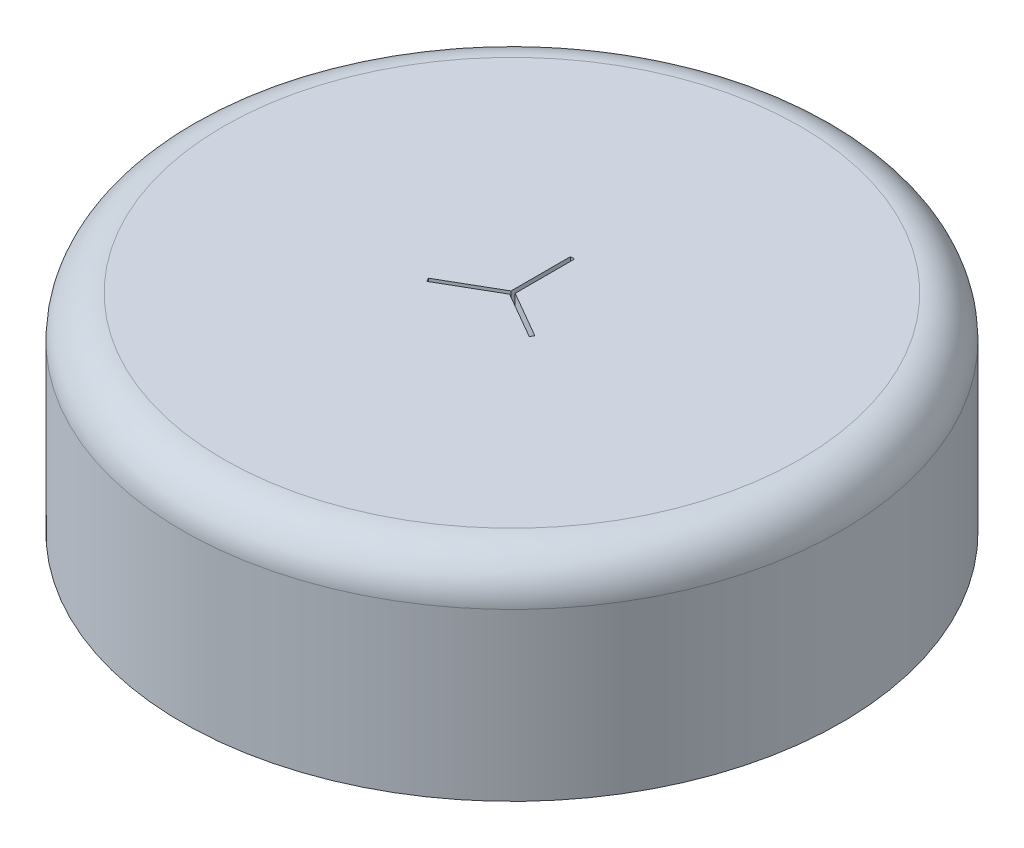
SolidWorks part; units mm, degrees
ref_plane "前视基准面" through (0, 0, 0) normal (0, 0, 1) x (1, 0, 0)
ref_plane "上视基准面" through (0, 0, 0) normal (0, 1, 0) x (1, 0, 0)
ref_plane "右视基准面" through (0, 0, 0) normal (1, 0, 0) x (0, 0, -1)
sketch "草图1" plane through (0, 0, 0) normal (0, 0, 1) x (1, 0, 0)
  line L2 (1.4, 3.5365) -> (0, 3.5365)
  line L3 (0, 3.5365) -> (0, 3.4565)
  line L4 (0, 3.4565) -> (1.0253, 3.4565)
  line L10 (0, -6.0383) -> (0, 6.0383) construction
  line L13 (1.2324, 3.0337) -> (1.2324, 3.2503)
  line L14 (1.2324, 3.2503) -> (1.3849, 3.2503)
  line L17 (1.2324, 3.0337) -> (1.0171, 3.0337)
  line L20 (1.4, 2.8626) -> (1.4, 2.5295)
  line L21 (1.4, 2.5295) -> (1.6, 2.5295)
  line L22 (1.6, 2.5295) -> (1.6, 3.3365)
  line L25 (1.0171, 3.0337) -> (1.0171, 2.8626)
  line L26 (1.0171, 2.8626) -> (1.4, 2.8626)
  arc A1 (1.4, 3.5365) -> (1.6, 3.3365) centre (1.4, 3.3365) cw
  arc A2 (1.3849, 3.2503) -> (1.0253, 3.4565) centre (1.0253, 3.0398) ccw
  point P15 (0, 0)
  dimension "D3" = 1.4
revolve "旋转1" add sketch "草图1" angle 360 about L10
ref_plane "基准面4" through (0, 3.5365, 0) normal (0, 1, 0) x (1, 0, 0)
sketch "草图2" plane through (0, 3.5365, 0) normal (0, 1, 0) x (1, 0, 0)
  line L0 (0, 0) -> (0, 0.2943) construction
  line L1 (0, 0) -> (-0.2593, -0.1497) construction
  line L2 (0, 0) -> (0.2311, -0.1334) construction
  line L3 (0, -0.0115) -> (-0.2543, -0.1584)
  line L4 (0.01, 0.0058) -> (0.2361, -0.1248)
  line L5 (-0.01, 0.0058) -> (-0.01, 0.2943)
  line L6 (-0.01, 0.0058) -> (-0.2643, -0.141)
  line L7 (0, -0.0115) -> (0.2261, -0.1421)
  line L8 (0.01, 0.0058) -> (0.01, 0.2943)
  line L9 (-0.2643, -0.141) -> (-0.2543, -0.1584)
  line L10 (0.2261, -0.1421) -> (0.2361, -0.1248)
  line L11 (0.01, 0.2943) -> (-0.01, 0.2943)
  line L13 (-0.005, 0.0087) -> (-0.2643, -0.141) construction
  line L14 (-0.01, 0) -> (-0.01, 0.2943) construction
  line L15 (0.005, 0.0087) -> (0.2361, -0.1248) construction
  line L16 (0.01, 0) -> (0.01, 0.2943) construction
  line L17 (0.005, -0.0087) -> (-0.2543, -0.1584) construction
  line L18 (-0.005, -0.0087) -> (0.2261, -0.1421) construction
  dimension "D1" = 120
  dimension "D2" = 120
  dimension "D3" = 0.01
  dimension "D4" = 0.01
extrude "切除-拉伸1" cut sketch "草图2" against normal blind 5
